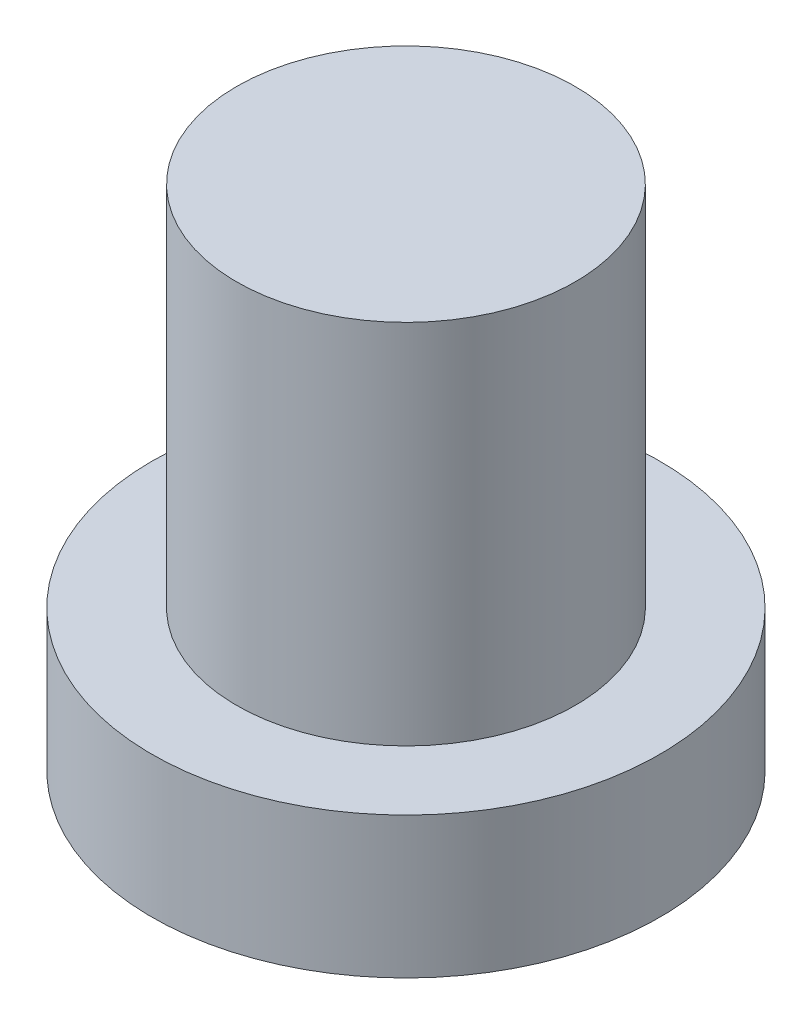
SolidWorks part; units mm, degrees
material "K110"
ref_plane "Front Plane" through (0, 0, 0) normal (0, 0, 1) x (1, 0, 0)
ref_plane "Top Plane" through (0, 0, 0) normal (0, 1, 0) x (1, 0, 0)
ref_plane "Right Plane" through (0, 0, 0) normal (1, 0, 0) x (0, 0, -1)
sketch "Sketch1" plane through (0, 0, 0) normal (0, 0, 1) x (1, 0, 0)
  line L0 (0, 0) -> (9, 0)
  line L1 (9, 0) -> (9, 5)
  line L2 (9, 5) -> (6, 5)
  line L3 (6, 5) -> (6, 18)
  line L4 (6, 18) -> (0, 18)
  line L5 (0, 18) -> (0, 0)
  line L6 (0, 23) -> (0, -5) construction
  point P9 (7.5, 5)
  dimension "D1" = 5
  dimension "D2" = 5
  dimension "D3" = 18
  dimension "D4" = 12
  dimension "D5" = 5
  dimension "D6" = 13
revolve "Revolve1" add sketch "Sketch1" angle 360 about L6
